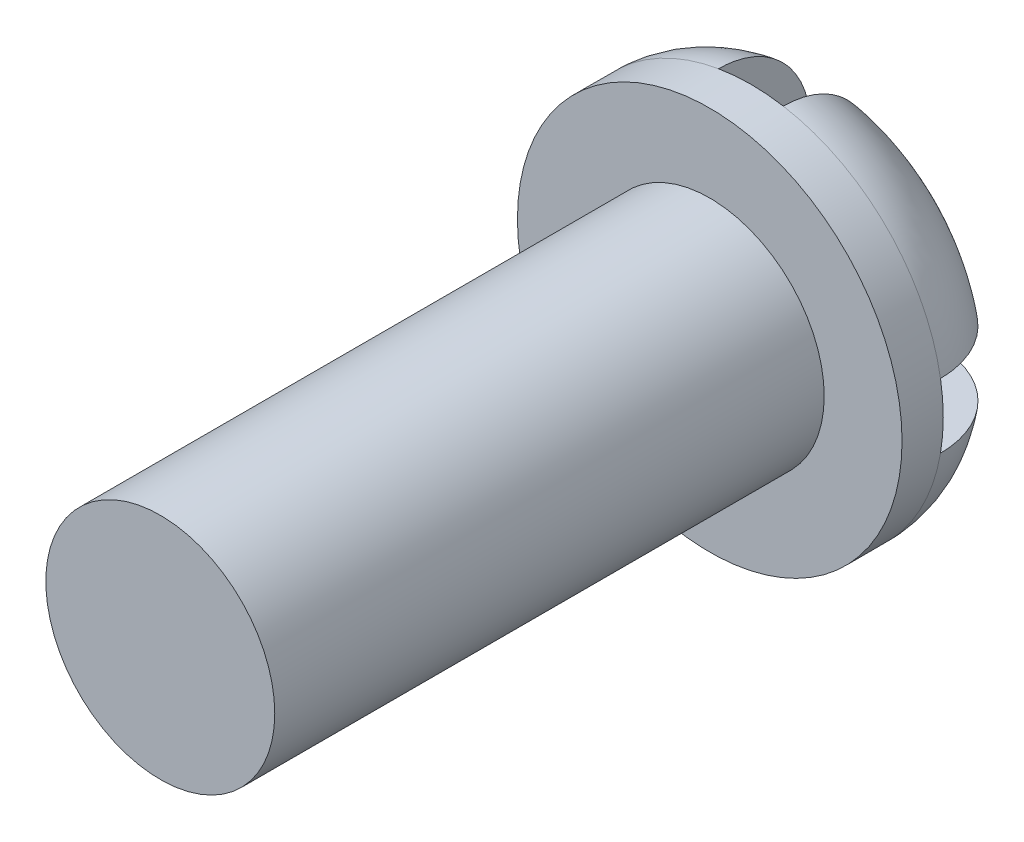
SolidWorks part; units mm, degrees
ref_plane "前视基准面" through (0, 0, 0) normal (0, 0, 1) x (1, 0, 0)
ref_plane "上视基准面" through (0, 0, 0) normal (0, 1, 0) x (1, 0, 0)
ref_plane "右视基准面" through (0, 0, 0) normal (1, 0, 0) x (0, 0, -1)
sketch "草图1" plane through (0, 0, 0) normal (0, 0, 1) x (1, 0, 0)
  circle A0 centre (0, 0) radius 2.5
  dimension "D1" = 5
extrude "凸台-拉伸1" add sketch "草图1" along normal blind 12
sketch "草图2" plane through (0, 0, 0) normal (0, 0, -1) x (-1, 0, 0)
  circle A0 centre (0, 0) radius 4.2
  dimension "D1" = 8.4
extrude "凸台-拉伸2" add sketch "草图2" along normal blind 2.9
fillet "圆角1" radius 2 1 edges at (-4.2, 0, -2.9)
sketch "草图3" plane through (0, 0, -2.9) normal (0, 0, -1) x (-1, 0, 0)
  line L0 (-0.7071, 0.7071) -> (-0.7071, 6.0064)
  line L1 (1, -1) -> (-1, -1) construction
  line L2 (1, -1) -> (1, 1) construction
  line L3 (1, 1) -> (-1, 1) construction
  line L4 (-1, -1) -> (-1, 1) construction
  line L5 (1, -1) -> (-1, 1) construction
  line L6 (1, 1) -> (-1, -1) construction
  line L7 (0.7071, 0.7071) -> (0.7071, 6.0064)
  line L8 (0.7071, 6.0064) -> (-0.7071, 6.0064)
  line L9 (0.7071, 0.7071) -> (6.0064, 0.7071)
  line L10 (0.7071, -0.7071) -> (6.0064, -0.7071)
  line L11 (6.0064, -0.7071) -> (6.0064, 0.7071)
  line L12 (0.7071, -0.7071) -> (0.7071, -6.0064)
  line L13 (-0.7071, -0.7071) -> (-0.7071, -6.0064)
  line L14 (-0.7071, -6.0064) -> (0.7071, -6.0064)
  line L15 (-0.7071, -0.7071) -> (-6.0064, -0.7071)
  line L16 (-0.7071, 0.7071) -> (-6.0064, 0.7071)
  line L17 (-6.0064, 0.7071) -> (-6.0064, -0.7071)
  circle A0 centre (0, 0) radius 1 construction
  dimension "D1" = 4
extrude "切除-拉伸1" cut sketch "草图3" against normal blind 2
